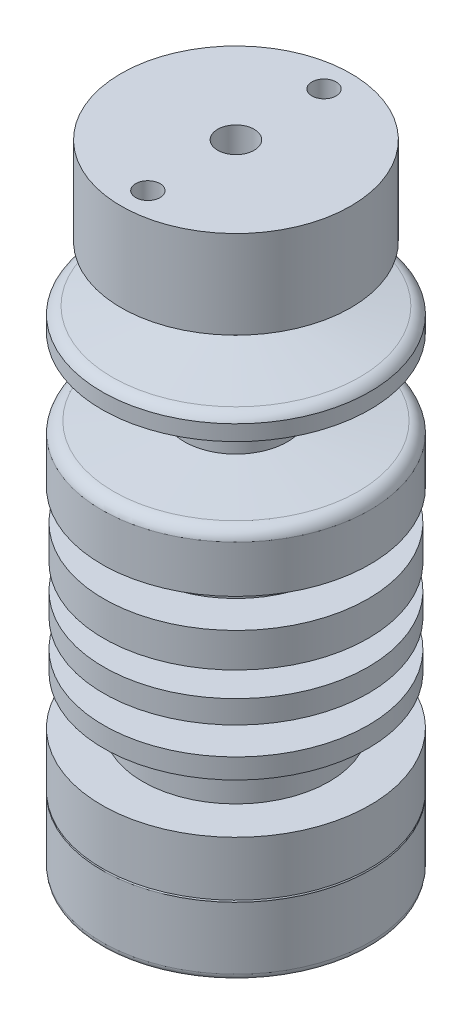
SolidWorks part; units mm, degrees
ref_plane "Alzado" through (0, 0, 0) normal (0, 0, 1) x (1, 0, 0)
ref_plane "Planta" through (0, 0, 0) normal (0, 1, 0) x (1, 0, 0)
ref_plane "Vista lateral" through (0, 0, 0) normal (1, 0, 0) x (0, 0, -1)
sketch "Croquis1" plane through (0, 0, 0) normal (0, 0, 1) x (1, 0, 0)
  line L0 (0, 0) -> (0, 43.0446) construction
  line L1 (0, 43.0446) -> (0, -121.9554) construction
  line L2 (0, 43.0446) -> (30, 43.0446)
  line L3 (30, 43.0446) -> (30, 20.0446)
  line L4 (30, 20.0446) -> (12.9858, 20.0446)
  line L5 (12.9858, 20.0446) -> (12.9858, 10.4062)
  line L6 (13.718, 8.5125) -> (32.3097, 5.486)
  line L7 (35, 3.5416) -> (35, -0.4901)
  line L8 (13.4687, -0.4901) -> (35, -0.4901)
  line L9 (13.4687, -0.4901) -> (13.4687, -18.5388)
  line L10 (13.4687, -18.5388) -> (31.9792, -20.5132)
  line L11 (35, -23.2242) -> (35, -35.5011)
  line L12 (24.3347, -77.3577) -> (34.5383, -77.3577)
  line L13 (24.3347, -77.3577) -> (24.3347, -104.2217)
  line L14 (24.3347, -104.2217) -> (34.5383, -104.2217)
  line L15 (35, -104.6833) -> (35, -120.9509)
  line L16 (34.7378, -121.991) -> (0, -121.9554)
  line L17 (0, 43.0446) -> (0, -121.9554)
  line L18 (34.5383, -77.3577) -> (34.5383, -72.1328)
  line L19 (35, -35.5011) -> (24.3347, -35.5011)
  line L20 (24.3347, -35.5011) -> (24.3347, -43.5201)
  line L21 (34.5383, -72.1328) -> (24.3347, -72.1328)
  line L22 (24.3347, -64.9174) -> (34.5383, -64.9174)
  line L23 (34.5383, -64.9174) -> (34.5383, -58.9461)
  line L24 (34.5383, -58.9461) -> (24.3347, -58.9461)
  line L25 (24.3347, -52.4771) -> (34.5383, -52.4771)
  line L26 (34.5383, -52.4771) -> (34.5383, -43.5201)
  line L27 (34.5383, -43.5201) -> (24.3347, -43.5201)
  line L28 (24.3347, -64.9174) -> (24.3347, -72.1328)
  line L29 (24.3347, -52.4771) -> (24.3347, -58.9461)
  arc A2 (12.9858, 10.4062) -> (13.718, 8.5125) centre (15.8008, 10.4062) ccw
  arc A3 (32.3097, 5.486) -> (35, 3.5416) centre (31.7144, 1.829) cw
  arc A6 (31.9792, -20.5132) -> (35, -23.2242) centre (31.6114, -23.9615) cw
  arc A8 (34.5383, -104.2217) -> (35, -104.6833) centre (34.5383, -104.6833) cw
  arc A9 (35, -120.9509) -> (34.7378, -121.991) centre (32.8058, -120.9509) cw
  point P3 (29.9547, 27.9358)
  point P7 (24.0859, -43.5201)
  point P8 (23.0907, -52.4771)
  point P9 (23.0907, -58.9461)
  point P42 (23.5883, -64.9174)
  point P45 (24.3347, -72.1328)
  point P46 (24.3347, -77.3577)
  dimension "D1" = 165
  dimension "D2" = 23
  dimension "D3" = 35
  dimension "D4" = 35
  dimension "D5" = 35
revolve "Revolución3" add sketch "Croquis1" angle 360 about L17
sketch "Croquis5" plane through (0, -104.2217, 0) normal (0, 1, 0) x (1, 0, 0)
  circle A0 centre (0.0979, 0) radius 7.9375
  dimension "D1" = 15.875
extrude "Cortar-Extruir3" cut sketch "Croquis5" against normal blind 18
ref_plane "Plano1" through (0, 0, 0) normal (1, 0, 0) x (0, 0, -1)
ref_plane "Plano2" through (0, 0, 0) normal (0, 0, 1) x (1, 0, 0)
sketch "Croquis9" plane through (0, 43.0446, 0) normal (0, 1, 0) x (1, 0, 0)
  line L0 (0, 0) -> (0, -23) construction
  line L1 (0, -38.5) -> (0, 38.5) construction
  line L2 (0, 0) -> (0, 23) construction
  circle A0 centre (0, 23) radius 3.175
  circle A1 centre (0, -23) radius 3.175
  dimension "D3" = 6.35
  dimension "D4" = 6.35
  dimension "D1" = 23
  dimension "D2" = 23
extrude "Cortar-Extruir5" cut sketch "Croquis9" against normal blind 18
sketch "Croquis10" plane through (0, 43.0446, 0) normal (0, 1, 0) x (1, 0, 0)
  circle A0 centre (0, 0) radius 4.765
  dimension "D1" = 9.53
extrude "Cortar-Extruir6" cut sketch "Croquis10" against normal blind 35
sketch "Croquis11" plane through (0, -104.2217, 0) normal (0, 1, 0) x (1, 0, 0)
  circle A0 centre (0, 0) radius 35
  dimension "D1" = 70
extrude "Saliente-Extruir1" add sketch "Croquis11" along normal blind 14.24
